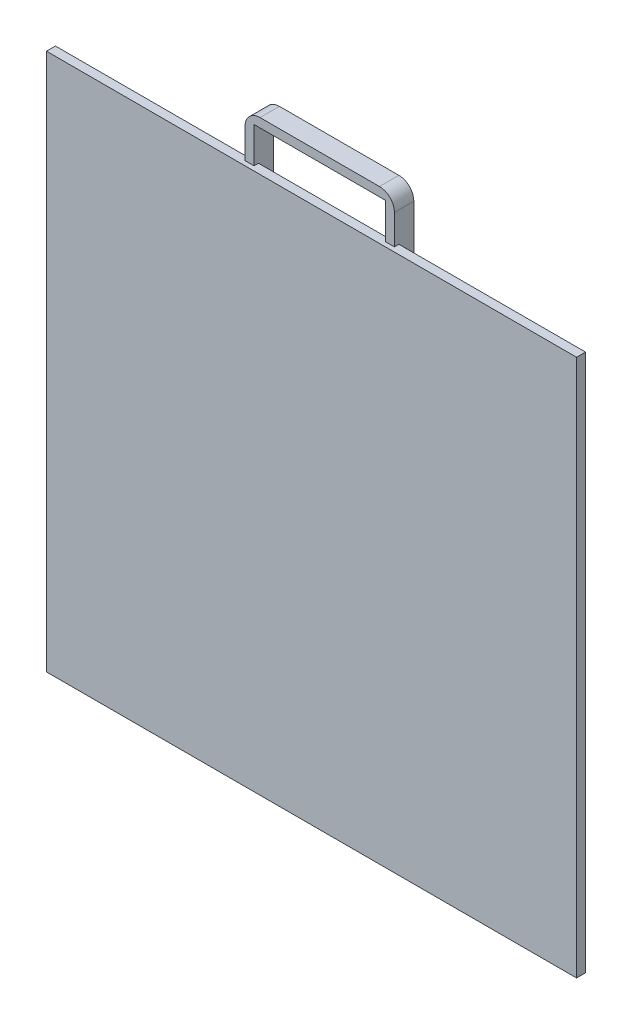
SolidWorks part; units mm, degrees
ref_plane "Front Plane" through (0, 0, 0) normal (0, 0, 1) x (1, 0, 0)
ref_plane "Top Plane" through (0, 0, 0) normal (0, 1, 0) x (1, 0, 0)
ref_plane "Right Plane" through (0, 0, 0) normal (1, 0, 0) x (0, 0, -1)
sketch "Sketch2" plane through (0, 0, 0) normal (0, 0, 1) x (1, 0, 0)
  line L0 (88.75, 180) -> (88.75, -61.1209) construction
  line L1 (0, 0) -> (177.5, 0)
  line L2 (0, 0) -> (0, 180)
  line L3 (0, 180) -> (177.5, 180)
  line L4 (177.5, 0) -> (177.5, 180)
  line L5 (-10.6813, 90) -> (212.4396, 90) construction
  dimension "D1" = 88.75
  dimension "D2" = 177.5
  dimension "D3" = 180
  dimension "D4" = 90
  dimension "D5" = 0
extrude "Boss-Extrude1" add sketch "Sketch2" against normal blind 3
ref_plane "Plane1" through (0, 0, -1.5) normal (0, 0, 1) x (1, 0, 0)
sketch "Sketch4" plane through (0, 0, -1.5) normal (0, 0, 1) x (1, 0, 0)
  line L0 (90, 186.0219) -> (90, -19.5231) construction
  line L5 (-6.3667, 90) -> (194.7013, 90) construction
  line L12 (68, 180) -> (112, 180)
  line L13 (115, 165) -> (65, 165)
  line L14 (115, 165) -> (115, 195)
  line L15 (115, 195) -> (65, 195)
  line L16 (65, 165) -> (65, 195)
  point P9 (90, 180)
  point P14 (90, 180)
  dimension "D7" = 44
  dimension "D8" = 30
  dimension "D10" = 50
  dimension "D11" = 25
  dimension "D12" = 22
extrude "Boss-Extrude2" add sketch "Sketch4" against normal blind 6.5
sketch "Sketch5" plane through (0, 0, -8) normal (0, 0, -1) x (-1, 0, 0)
  line L0 (-90, 208.2354) -> (-90, 145.7774) construction
  line L1 (-115, 180) -> (-44.8308, 180) construction
  line L2 (-115, 165) -> (-115, 195) construction
  line L3 (-65, 180) -> (0, 180) construction
  line L4 (-112, 168) -> (-112, 165)
  line L6 (-112, 168) -> (-112, 192)
  line L7 (-112, 192) -> (-68, 192)
  line L8 (-68, 168) -> (-68, 192)
  line L9 (-112, 168) -> (-68, 192) construction
  line L10 (-112, 192) -> (-68, 168) construction
  line L11 (-115, 165) -> (-65, 165) construction
  line L12 (-68, 168) -> (-68, 165)
  line L13 (-112, 165) -> (-68, 165)
  point P8 (-90, 180)
  dimension "D1" = 44
  dimension "D2" = 24
  dimension "D3" = 22
  dimension "D4" = 12
extrude "Cut-Extrude1" cut sketch "Sketch5" against normal up to surface (5 mm away) up to face at (89.375, 131.25, -3)
sketch "Sketch6" plane through (0, 0, -1.5) normal (0, 0, 1) x (1, 0, 0)
  line L0 (90, 199.2044) -> (90, 162.7937) construction
  line L1 (65, 180) -> (65, 195) construction
  line L4 (68, 192) -> (112, 192)
  line L6 (68, 192) -> (68, 180)
  line L7 (65, 180) -> (115, 180) construction
  line L9 (112, 180) -> (112, 192)
  line L11 (68, 180) -> (112, 180)
  point P2 (90, 180.999)
  dimension "D1" = 44
  dimension "D2" = 25
  dimension "D3" = 12
extrude "Cut-Extrude2" cut sketch "Sketch6" against normal blind 6.5
fillet "Fillet1" radius 5 1 edges at (115, 195, -4.75)
fillet "Fillet2" radius 5 1 edges at (65, 195, -4.75)
